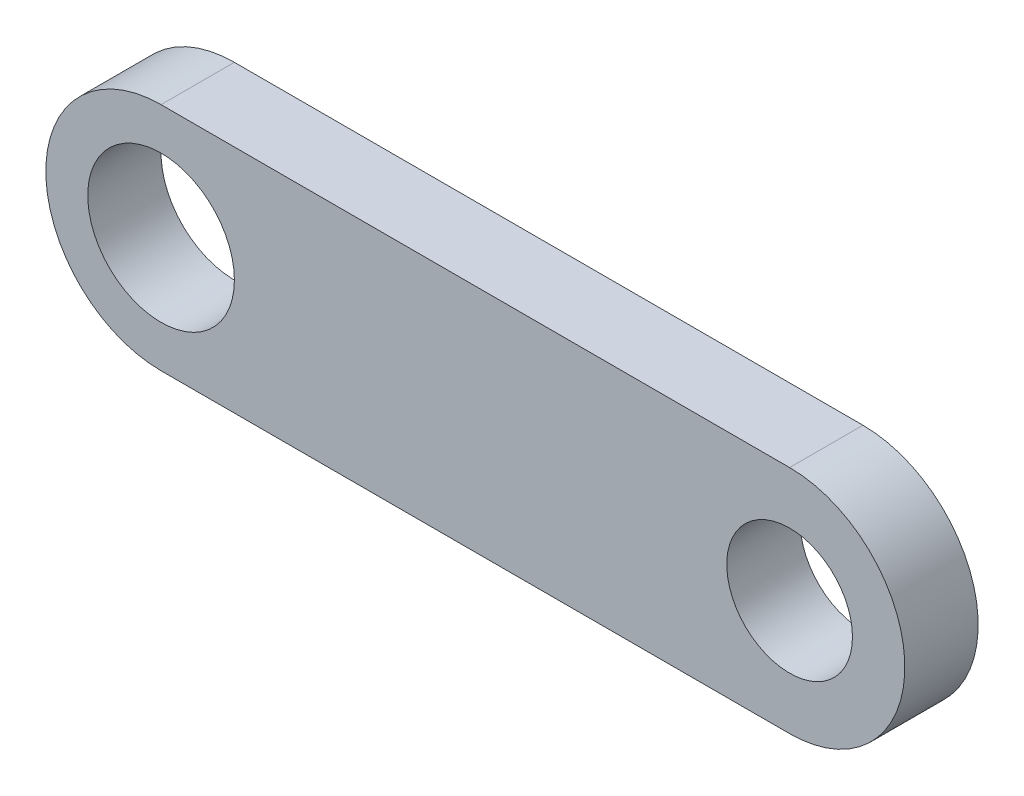
SolidWorks part; units mm, degrees
ref_plane "Front Plane" through (0, 0, 0) normal (0, 0, 1) x (1, 0, 0)
ref_plane "Top Plane" through (0, 0, 0) normal (0, 1, 0) x (1, 0, 0)
ref_plane "Right Plane" through (0, 0, 0) normal (1, 0, 0) x (0, 0, -1)
sketch "Sketch1" plane through (0, 0, 0) normal (0, 0, 1) x (1, 0, 0)
  line L0 (0, 5.5) -> (30, 5.5)
  line L1 (0, -5.5) -> (30, -5.5)
  circle A0 centre (0, 0) radius 3.5
  arc A1 (0, 5.5) -> (0, -5.5) centre (0, 0) ccw
  arc A2 (30, -5.5) -> (30, 5.5) centre (30, 0) ccw
  circle A3 centre (30, 0) radius 3
  circle A5 centre (0, 0) radius 5.5 construction
  point P8 (3.1, 0)
  dimension "D1" = 7
  dimension "D4" = 6
  dimension "D3" = 30
  dimension "D2" = 2
extrude "Boss-Extrude1" add sketch "Sketch1" along normal blind 3.5
